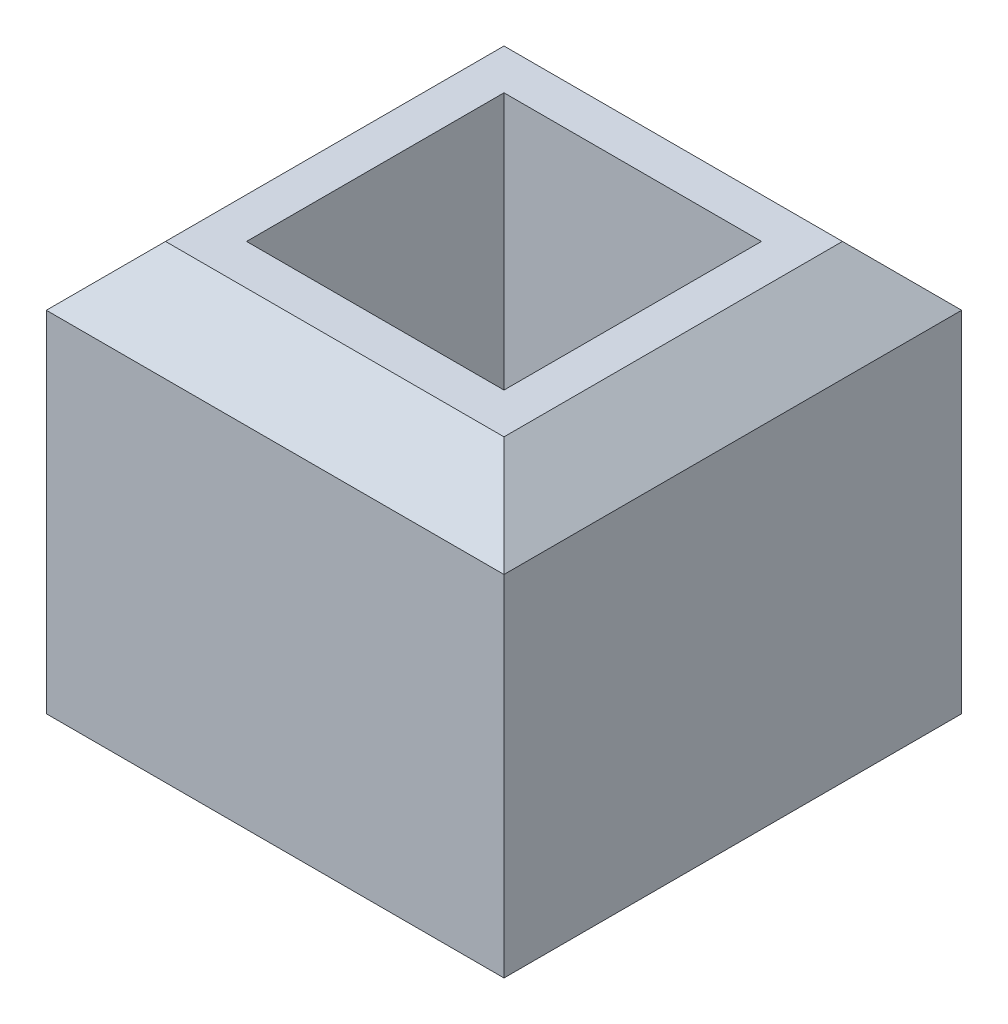
SolidWorks part; units mm, degrees
ref_plane "Front Plane" through (0, 0, 0) normal (0, 0, 1) x (1, 0, 0)
ref_plane "Top Plane" through (0, 0, 0) normal (0, 1, 0) x (1, 0, 0)
ref_plane "Right Plane" through (0, 0, 0) normal (1, 0, 0) x (0, 0, -1)
sketch "Sketch2" plane through (0, 0, 0) normal (0, 1, 0) x (1, 0, 0)
  line L1 (-1.7145, 1.7145) -> (1.7145, 1.7145)
  line L2 (-1.7145, 1.7145) -> (-1.7145, -1.7145)
  line L3 (-1.7145, -1.7145) -> (1.7145, -1.7145)
  line L4 (1.7145, 1.7145) -> (1.7145, -1.7145)
  line L5 (-1.7145, 1.7145) -> (1.7145, -1.7145) construction
  line L6 (-1.7145, -1.7145) -> (1.7145, 1.7145) construction
  line L7 (-3.048, 3.048) -> (3.048, 3.048)
  line L8 (-3.048, 3.048) -> (-3.048, -3.048)
  line L9 (-3.048, -3.048) -> (3.048, -3.048)
  line L10 (3.048, 3.048) -> (3.048, -3.048)
  line L11 (-3.048, 3.048) -> (3.048, -3.048) construction
  line L12 (-3.048, -3.048) -> (3.048, 3.048) construction
  point P0 (0, 0)
  point P5 (0, 0)
  dimension "D1" = 6.096
  dimension "D2" = 6.096
  dimension "D3" = 3.429
  dimension "D4" = 3.429
extrude "Boss-Extrude1" add sketch "Sketch2" along normal blind 5.4483
chamfer "Chamfer1" distance 0.7937 angle 45 4 edges at (-3.048, 5.4483, 0) (0, 5.4483, -3.048) (3.048, 5.4483, 0) (0, 5.4483, 3.048)
